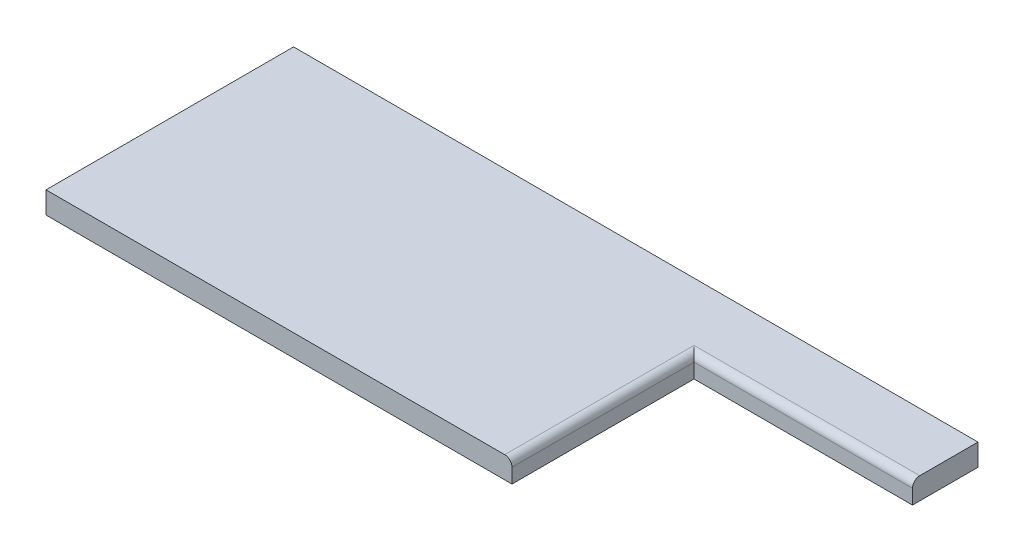
SolidWorks part; units mm, degrees
material "Pine"
ref_plane "Front Plane" through (0, 0, 0) normal (0, 0, 1) x (1, 0, 0)
ref_plane "Top Plane" through (0, 0, 0) normal (0, 1, 0) x (1, 0, 0)
ref_plane "Right Plane" through (0, 0, 0) normal (1, 0, 0) x (0, 0, -1)
sketch "Sketch1" plane through (0, 0, 0) normal (0, 1, 0) x (1, 0, 0)
  line L1 (0, 0) -> (188, 0)
  line L2 (0, 0) -> (0, 68)
  line L3 (0, 68) -> (188, 68)
  line L4 (188, 0) -> (188, 68)
  dimension "D1" = 188
  dimension "D2" = 68
extrude "Boss-Extrude1" add sketch "Sketch1" along normal blind 6
sketch "Sketch2" plane through (0, 6, 0) normal (0, 1, 0) x (1, 0, 0)
  line L0 (188, 0) -> (188, 68) construction
  line L1 (188, 50) -> (128, 50)
  line L2 (188, 50) -> (188, 0)
  line L3 (188, 0) -> (128, 0)
  line L4 (128, 50) -> (128, 0)
  line L5 (0, 0) -> (188, 0) construction
  dimension "D1" = 50
  dimension "D2" = 60
extrude "Cut-Extrude1" cut sketch "Sketch2" against normal through all
fillet "Fillet2" radius 2 2 edges at (128, 6, -25) (158, 6, -50)
equation "\"BoardThickness\"= 6"
equation "\"D1@Sketch1\"=200-\"BoardThickness\"*2"
equation "\"D2@Sketch1\"=100-20-\"BoardThickness\"*2"
equation "\"D1@Boss-Extrude1\"=\"BoardThickness\""
